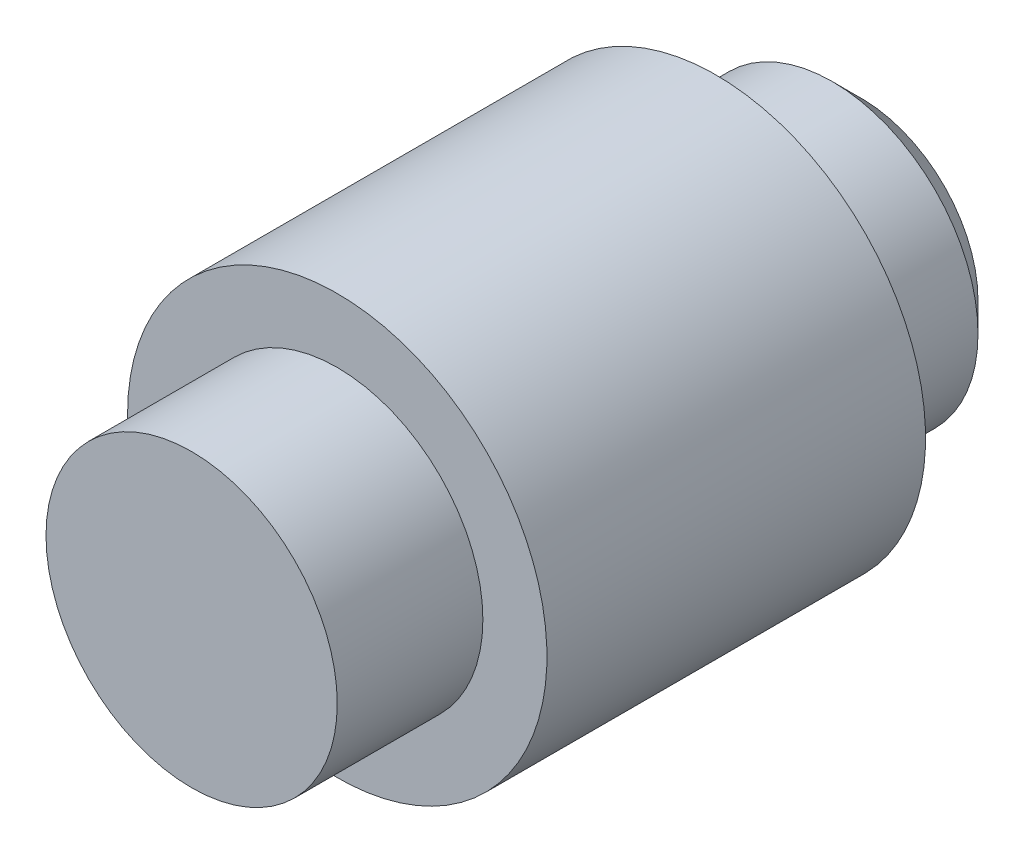
SolidWorks part; units mm, degrees
ref_plane "Front Plane" through (0, 0, 0) normal (0, 0, 1) x (1, 0, 0)
ref_plane "Top Plane" through (0, 0, 0) normal (0, 1, 0) x (1, 0, 0)
ref_plane "Right Plane" through (0, 0, 0) normal (1, 0, 0) x (0, 0, -1)
sketch "Sketch2" plane through (0, 0, 0) normal (0, 0, 1) x (1, 0, 0)
  circle A0 centre (0, 0) radius 1.25
  dimension "D1" = 2.5
sketch "Sketch3" plane through (0, 0, 0) normal (0, 0, 1) x (1, 0, 0)
  line L5 (-3.6, 3.6) -> (3.6, 3.6) construction
  line L6 (-3.6, 3.6) -> (-3.6, -3.6) construction
  line L7 (-3.6, -3.6) -> (3.6, -3.6) construction
  line L8 (3.6, 3.6) -> (3.6, -3.6) construction
  circle A0 centre (0, 0) radius 3.6
  point P4 (0, 3.6)
  point P6 (-3.6, 0)
  dimension "D1" = 7.2
extrude "Boss-Extrude1" add sketch "Sketch3" along normal blind 6.5
sketch "Sketch4" plane through (0, 0, 0) normal (0, 0, 1) x (1, 0, 0)
  circle A0 centre (0, 0) radius 2.5
  dimension "D1" = 5
extrude "Boss-Extrude2" add sketch "Sketch4" against normal blind 2.5
sketch "Sketch5" plane through (0, 0, 6.5) normal (0, 0, 1) x (1, 0, 0)
  circle A0 centre (0, 0) radius 2.5
  dimension "D1" = 5
extrude "Boss-Extrude3" add sketch "Sketch5" along normal blind 2.5
chamfer "Chamfer1" distance 0.5 angle 45 1 edges at (2.5, 0, -2.5)
equation "\"length\"=6.5"
equation "\"D1@Boss-Extrude1\"=\"length\""
equation "\"hole\"=5"
equation "\"D1@Sketch5\"=\"hole\""
equation "\"D1@Sketch4\"=\"hole\""
